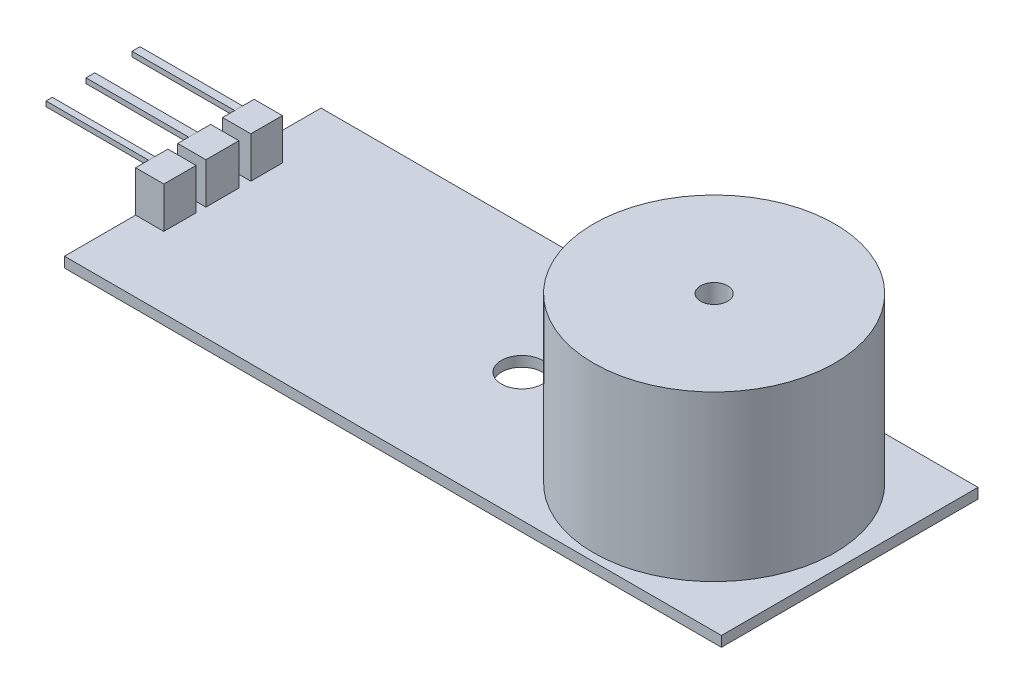
SolidWorks part; units mm, degrees
ref_plane "Front Plane" through (0, 0, 0) normal (0, 0, 1) x (1, 0, 0)
ref_plane "Top Plane" through (0, 0, 0) normal (0, 1, 0) x (1, 0, 0)
ref_plane "Right Plane" through (0, 0, 0) normal (1, 0, 0) x (0, 0, -1)
other "Center of Mass"
sketch "Sketch1" plane through (0, 0, 0) normal (0, 1, 0) x (1, 0, 0)
  line L1 (0, 0) -> (32, 0)
  line L2 (0, 0) -> (0, 12.5)
  line L3 (0, 12.5) -> (32, 12.5)
  line L4 (32, 0) -> (32, 12.5)
  dimension "D1" = 32
  dimension "D2" = 12.5
extrude "Boss-Extrude1" add sketch "Sketch1" along normal blind 0.5
sketch "Sketch2" plane through (0, 0.5, 0) normal (0, 1, 0) x (1, 0, 0)
  line L0 (0, 6.25) -> (32, 6.25) construction
  line L1 (0, 12.5) -> (0, 0) construction
  line L2 (32, 0) -> (32, 12.5) construction
  circle A0 centre (25.3966, 6.25) radius 5.8772
extrude "Boss-Extrude3" add sketch "Sketch2" along normal blind 8 separate body
sketch "Sketch4" plane through (0, 0.5, 0) normal (0, 1, 0) x (1, 0, 0)
  circle A0 centre (16.0342, 6.25) radius 1
  dimension "D1" = 2
extrude "Cut-Extrude1" cut sketch "Sketch4" against normal blind 8
sketch "Sketch5" plane through (0, 0.5, 0) normal (0, 1, 0) x (1, 0, 0)
  line L0 (0, 6.25) -> (32, 6.25) construction
  line L1 (0, 12.5) -> (0, 0) construction
  line L2 (32, 0) -> (32, 12.5) construction
  line L4 (0, 7.1213) -> (1.3754, 7.1213)
  line L5 (0, 7.1213) -> (0, 5.5154)
  line L6 (0, 5.5154) -> (1.3754, 5.5154)
  line L7 (1.3754, 7.1213) -> (1.3754, 5.5154)
  line L8 (0, 7.7022) -> (1.3754, 7.7022)
  line L9 (0, 7.7022) -> (0, 9.2398)
  line L10 (0, 9.2398) -> (1.3754, 9.2398)
  line L11 (1.3754, 7.7022) -> (1.3754, 9.2398)
  line L12 (0, 5.037) -> (1.3754, 5.037)
  line L13 (0, 5.037) -> (0, 3.4652)
  line L14 (0, 3.4652) -> (1.3754, 3.4652)
  line L15 (1.3754, 5.037) -> (1.3754, 3.4652)
extrude "Boss-Extrude4" add sketch "Sketch5" along normal blind 2 separate body
sketch "Sketch6" plane through (0, 0, 0) normal (-1, 0, 0) x (0, 0, 1)
  line L0 (-9.2398, 2.5) -> (-7.7022, 2.5) construction
  line L1 (-8.6792, 2.5) -> (-8.2922, 2.5)
  line L2 (-8.6792, 2.5) -> (-8.6792, 2.2545)
  line L3 (-8.6792, 2.2545) -> (-8.2922, 2.2545)
  line L4 (-8.2922, 2.5) -> (-8.2922, 2.2545)
  line L5 (-7.1213, 2.5) -> (-5.5154, 2.5) construction
  line L6 (-6.4769, 2.5) -> (-6.0498, 2.5)
  line L7 (-6.4769, 2.5) -> (-6.4769, 2.2545)
  line L8 (-6.4769, 2.2545) -> (-6.0498, 2.2545)
  line L9 (-6.0498, 2.5) -> (-6.0498, 2.2545)
  line L10 (-5.037, 2.5) -> (-3.4652, 2.5) construction
  line L11 (-4.408, 2.5) -> (-4.1011, 2.5)
  line L12 (-4.408, 2.5) -> (-4.408, 2.2545)
  line L13 (-4.408, 2.2545) -> (-4.1011, 2.2545)
  line L14 (-4.1011, 2.5) -> (-4.1011, 2.2545)
extrude "Boss-Extrude5" add sketch "Sketch6" along normal blind 5 separate body
sketch "Sketch7" plane through (0, 8.5, 0) normal (0, 1, 0) x (1, 0, 0)
  circle A0 centre (25.3966, 6.25) radius 0.6585
extrude "Cut-Extrude2" cut sketch "Sketch7" against normal blind 5
